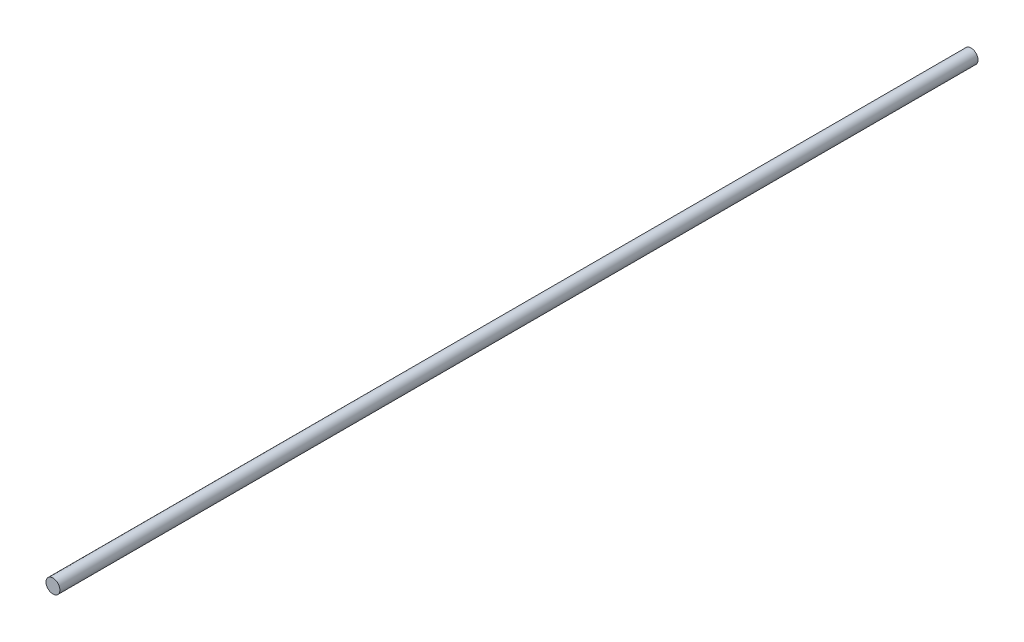
SolidWorks part; units mm, degrees
ref_plane "Plan de face" through (0, 0, 0) normal (0, 0, 1) x (1, 0, 0)
ref_plane "Plan de dessus" through (0, 0, 0) normal (0, 1, 0) x (1, 0, 0)
ref_plane "Plan de droite" through (0, 0, 0) normal (1, 0, 0) x (0, 0, -1)
sketch "Esquisse1" plane through (0, 0, 0) normal (0, 0, 1) x (1, 0, 0)
  circle A0 centre (0, 0) radius 5
  dimension "D1" = 10
extrude "Boss.-Extru.1" add sketch "Esquisse1" along normal blind 660
